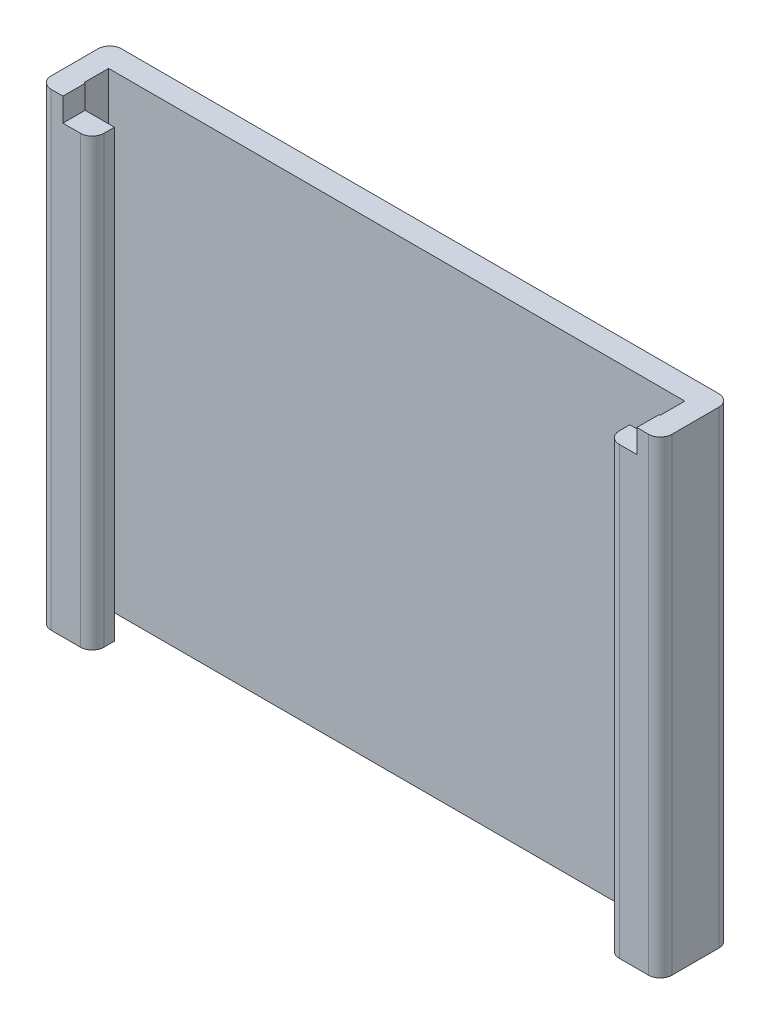
SolidWorks part; units mm, degrees
ref_plane "Front Plane" through (0, 0, 0) normal (0, 0, 1) x (1, 0, 0)
ref_plane "Top Plane" through (0, 0, 0) normal (0, 1, 0) x (1, 0, 0)
ref_plane "Right Plane" through (0, 0, 0) normal (1, 0, 0) x (0, 0, -1)
sketch "Sketch1" plane through (0, 0, 0) normal (0, 1, 0) x (1, 0, 0)
  line L1 (26.5, 2) -> (-26.5, 2)
  line L2 (-26.5, 2) -> (-26.5, -4)
  line L3 (-26.5, -4) -> (-22, -4)
  line L4 (-22, -4) -> (-22, -2)
  line L5 (-22, -2) -> (-24.5, -2)
  line L6 (24.5, 0) -> (-24.5, 0)
  line L7 (-24.5, 0) -> (-24.5, -2)
  line L8 (0, 0) -> (0, -9.0675) construction
  line L9 (26.5, 2) -> (26.5, -4)
  line L10 (26.5, -4) -> (22, -4)
  line L11 (22, -4) -> (22, -2)
  line L12 (22, -2) -> (24.5, -2)
  line L13 (24.5, 0) -> (24.5, -2)
  point P9 (-24.5, -1)
  dimension "D2" = 2
  dimension "D3" = 2.5
  dimension "D4" = 6
  dimension "D6" = 2
extrude "Boss-Extrude1" add sketch "Sketch1" along normal blind 40 contours L7 L5 L4 L3 L2 L1 L9 L10 L11 L12 L13 L6
sketch "Sketch2" plane through (0, 0, 0) normal (0, 1, 0) x (1, 0, 0)
  line L0 (0, 0) -> (0, -17.2218) construction
  line L5 (24.5, -2) -> (22, -2)
  line L6 (22, 0) -> (22, -2)
  line L7 (24.5, 0) -> (22, 0)
  line L8 (24.5, 0) -> (24.5, -2)
  line L9 (-22, -4) -> (-22, -2) construction
  line L10 (-24.5, 0) -> (-22, 0)
  line L11 (-24.5, 0) -> (-24.5, -2.1)
  line L12 (-24.5, -2.1) -> (-22, -2.1)
  line L13 (-22, 0) -> (-22, -2.1)
  line L14 (24.5, 0) -> (-24.5, 0) construction
  point P4 (22, 0)
  dimension "D1" = 2.1
fillet "Fillet1" radius 1 6 edges at (22, 20, 4) (-22, 20, 4) (26.5, 20, -2) (26.5, 20, 4) (-26.5, 20, -2) (-26.5, 20, 4)
sketch "Sketch3" plane through (0, 40, 0) normal (0, 1, 0) x (1, 0, 0)
  line L0 (0, 0) -> (0, -13.3163) construction
  line L3 (-24.5, -4.8249) -> (-21.4403, -4.8249)
  line L5 (24.5, 0) -> (-24.5, 0) construction
  line L6 (24.5, -4.8249) -> (21.4403, -4.8249)
  line L7 (24.5, -2) -> (24.5, -4.8249)
  line L8 (24.5, -2) -> (21.4403, -2)
  line L9 (21.4403, -2) -> (21.4403, -4.8249)
  line L10 (-24.5, -4.8249) -> (-24.5, -2.1)
  line L11 (-24.5, -2.1) -> (-21.3439, -2.1)
  line L12 (-21.3439, -2.1) -> (-21.4403, -4.8249)
extrude "Cut-Extrude1" cut sketch "Sketch3" against normal blind 2
extrude "Cut-Extrude2" cut sketch "Sketch2" along normal blind 45
mirror "Mirror1" about plane through (0, 0, 0) normal (1, 0, 0) of "Cut-Extrude2"
sketch "Sketch6" plane through (0, 40, 0) normal (0, 1, 0) x (1, 0, 0)
  line L0 (0, -3.3) -> (0, 3.3) construction
  line L1 (-24.5, 0) -> (-24.6, 0)
  line L2 (-24.5, 0) -> (-24.5, -2.1)
  line L3 (-24.5, -2.1) -> (-24.6, -2.1)
  line L4 (-24.6, 0) -> (-24.6, -2.1)
  line L5 (24.5, -2.1) -> (24.6, -2.1)
  line L6 (24.6, 0) -> (24.6, -2.1)
  line L7 (24.5, 0) -> (24.6, 0)
  line L8 (24.5, 0) -> (24.5, -2.1)
  point P5 (0, 0)
  point P13 (0, 0)
  dimension "D1" = 0.1
extrude "Cut-Extrude3" cut sketch "Sketch6" against normal blind 40
